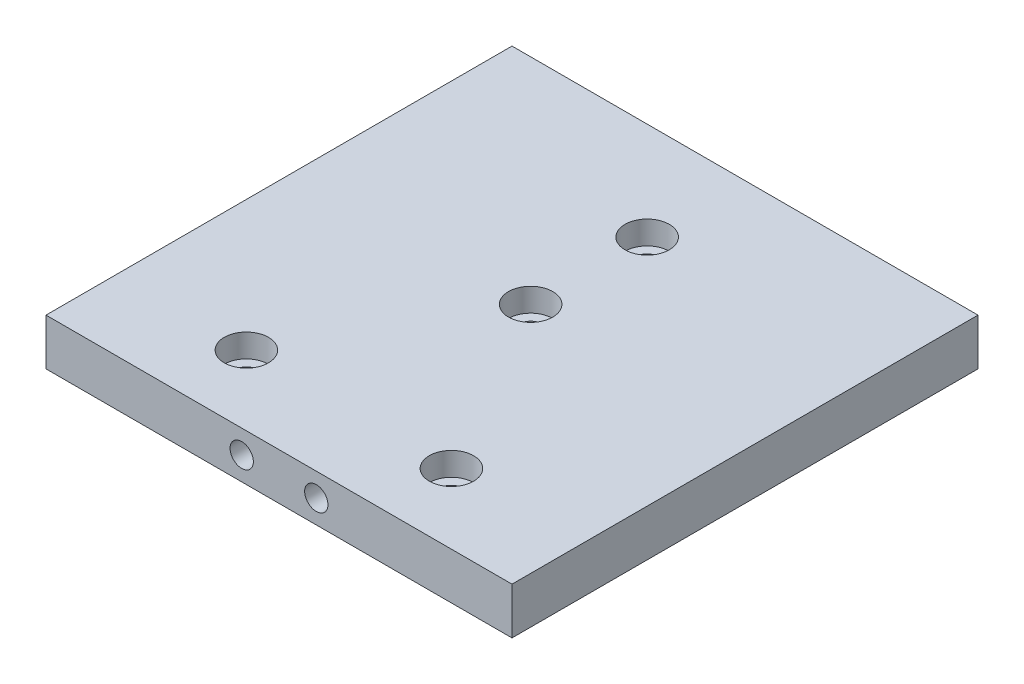
SolidWorks part; units mm, degrees
ref_plane "정면" through (0, 0, 0) normal (0, 0, 1) x (1, 0, 0)
ref_plane "윗면" through (0, 0, 0) normal (0, 1, 0) x (1, 0, 0)
ref_plane "우측면" through (0, 0, 0) normal (1, 0, 0) x (0, 0, -1)
sketch "스케치1" plane through (0, 0, 0) normal (0, 1, 0) x (1, 0, 0)
  line L1 (50, -50) -> (-50, -50)
  line L2 (50, -50) -> (50, 50)
  line L3 (50, 50) -> (-50, 50)
  line L4 (-50, -50) -> (-50, 50)
  line L5 (50, -50) -> (-50, 50) construction
  line L6 (50, 50) -> (-50, -50) construction
  point P0 (0, 0)
  dimension "D1" = 100
  dimension "D2" = 100
extrude "보스-돌출1" add sketch "스케치1" along normal blind 10
hole_wizard "M2 소켓 머리 캡 나사용 카운터보어1" positions "스케치2" profile "스케치4" counterbore size "M2" standard "KS"
sketch "스케치2" plane through (0, 0, 50) normal (0, 0, 1) x (1, 0, 0)
  line L1 (-50, 5) -> (50, 5) construction
  line L2 (-50, 10) -> (-50, 0) construction
  line L3 (50, 10) -> (50, 0) construction
  line L4 (0, 10) -> (0, 0) construction
  line L5 (-50, 10) -> (50, 10) construction
  line L6 (-50, 0) -> (50, 0) construction
  point P0 (-8, 5)
  point P2 (8, 5)
  dimension "D1" = 42
sketch "스케치4" plane through (-8, 5, 50) normal (1, 0, 0) x (0, -1, 0)
  line L0 (0, 0) -> (0, 70)
  line L1 (0, 70) -> (1.5, 70)
  line L2 (1.5, 70) -> (1.5, 10)
  line L3 (1.5, 10) -> (2.5, 10)
  line L4 (2.5, 10) -> (2.5, 0)
  line L5 (2.5, 0) -> (0, 0)
  line L10 (0, 70) -> (-1.5, 70) construction
  line L11 (0, -6.35) -> (0, 107.95) construction
  dimension "구멍 지름" = 3
  dimension "구멍 깊이" = 70
  dimension "카운터보어 지름" = 5
  dimension "카운터보어 깊이" = 10
  dimension "드릴 각도" = 180
hole_wizard "M5 소켓 머리 캡 나사용 카운터보어1" positions "스케치9" profile "스케치10" counterbore size "M5" standard "KS" end condition through all
sketch "스케치9" plane through (0, 10, 0) normal (0, 1, 0) x (1, 0, 0)
  line L0 (0, 50) -> (0, -50) construction
  line L1 (50, 50) -> (-50, 50) construction
  line L2 (-50, -50) -> (50, -50) construction
  line L4 (-50, 50) -> (-50, -50) construction
  point P0 (0, 29)
  point P2 (0, 4)
  point P4 (-22, -35)
  point P6 (22, -35)
  dimension "D1" = 15
  dimension "D2" = 54
  dimension "D3" = 79
  dimension "D4" = 28
sketch "스케치10" plane through (0, 10, -29) normal (1, 0, 0) x (0, 0, 1)
  line L0 (0, 0) -> (0, 10)
  line L1 (0, 10) -> (2.65, 10)
  line L3 (2.65, 10) -> (2.65, 5)
  line L4 (2.65, 5) -> (4.75, 5)
  line L5 (4.75, 5) -> (4.75, 0)
  line L7 (4.75, 0) -> (0, 0)
  line L11 (0, -6.35) -> (0, 107.95) construction
  dimension "관통 구멍 지름" = 5.3
  dimension "관통 구멍 깊이" = 10
  dimension "카운터보어 지름" = 9.5
  dimension "카운터보어 깊이" = 5
hole_wizard "M2 여유 구멍2" positions "스케치13" profile "스케치14" hole size "M2" standard "KS"
sketch "스케치13" plane through (0, 0, 0) normal (0, -1, 0) x (-1, 0, 0)
  line L0 (0, 50) -> (0, -50) construction
  line L1 (-50, 50) -> (50, 50) construction
  line L2 (50, -50) -> (-50, -50) construction
  line L3 (-50, -50) -> (-50, 50) construction
  point P0 (-8, -35)
  point P2 (8, -35)
  point P4 (8, 16.5)
  point P6 (-8, 16.5)
  dimension "D1" = 42
  dimension "D2" = 15
  dimension "D3" = 66.5
sketch "스케치14" plane through (8, 0, 35) normal (1, 0, 0) x (0, 0, -1)
  line L0 (0, 0) -> (0, 8)
  line L1 (0, 8) -> (1, 8)
  line L2 (1, 8) -> (1, 0)
  line L5 (1, 0) -> (0, 0)
  line L10 (0, 8) -> (-1, 8) construction
  line L11 (0, -6.35) -> (0, 107.95) construction
  dimension "구멍 지름" = 2
  dimension "구멍 깊이" = 8
  dimension "드릴 각도" = 180
